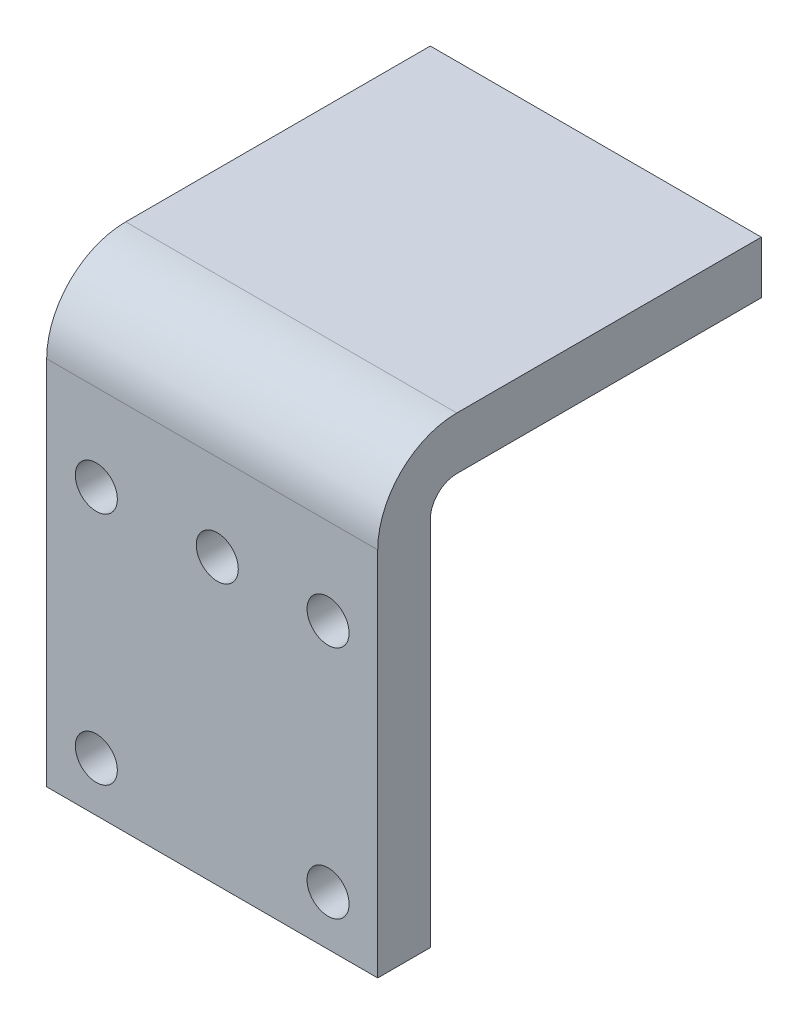
SolidWorks part; units mm, degrees
material "Hierro dúctil"
ref_plane "Alzado" through (0, 0, 0) normal (0, 0, 1) x (1, 0, 0)
ref_plane "Planta" through (0, 0, 0) normal (0, 1, 0) x (1, 0, 0)
ref_plane "Vista lateral" through (0, 0, 0) normal (1, 0, 0) x (0, 0, -1)
sketch "Croquis1" plane through (0, 0, 0) normal (1, 0, 0) x (0, 0, -1)
  line L0 (8, 0) -> (100, 0)
  line L1 (55, 0) -> (-55, 0) construction
  line L2 (0, -8) -> (0, -120)
  line L3 (-15.875, -8) -> (-15.875, -120)
  line L4 (8, 15.875) -> (100, 15.875)
  line L5 (100, 0) -> (100, 15.875)
  line L6 (0, -120) -> (-15.875, -120)
  arc A0 (8, 0) -> (0, -8) centre (8, -8) ccw
  arc A1 (8, 15.875) -> (-15.875, -8) centre (8, -8) ccw
  point P8 (0, 0)
  dimension "D1" = 8
  dimension "D2" = 15.875
extrude "Saliente-Extruir1" add sketch "Croquis1" along normal blind 100
sketch "Croquis2" plane through (0, 0, 15.875) normal (0, 0, 1) x (1, 0, 0)
  line L0 (0, -8) -> (0, -120) construction
  line L1 (100, -8) -> (100, -120) construction
  line L2 (100, -120) -> (0, -120) construction
  circle A0 centre (15, -34.0899) radius 6.35
  circle A1 centre (85, -34.0899) radius 6.35
  circle A2 centre (15, -105) radius 6.35
  circle A3 centre (85, -105) radius 6.35
  circle A4 centre (51.5322, -34.0899) radius 6.35
  dimension "D1" = 15
  dimension "D2" = 15
  dimension "D3" = 15
  dimension "D4" = 15
extrude "Cortar-Extruir1" cut sketch "Croquis2" against normal blind 100
